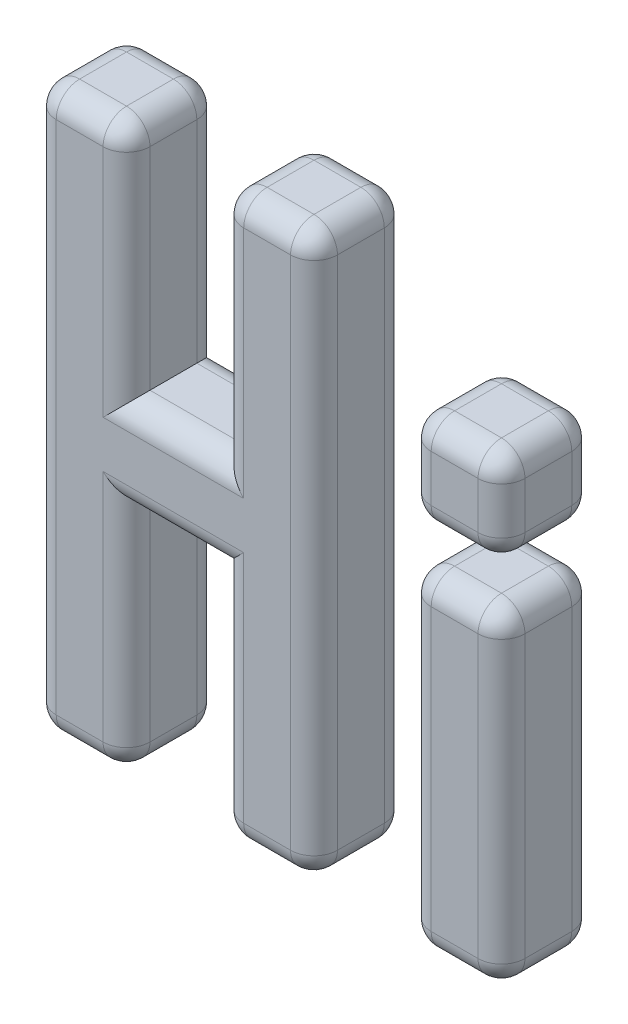
SolidWorks part; units mm, degrees
material "Galvanized Steel"
ref_plane "Front Plane" through (0, 0, 0) normal (0, 0, 1) x (1, 0, 0)
ref_plane "Top Plane" through (0, 0, 0) normal (0, 1, 0) x (1, 0, 0)
ref_plane "Right Plane" through (0, 0, 0) normal (1, 0, 0) x (0, 0, -1)
sketch "Sketch1" plane through (0, 0, 0) normal (0, 0, 1) x (1, 0, 0)
  line L0 (-86.338, 15.2817) -> (-86.338, -9.7183)
  line L1 (-96.338, 50.2817) -> (-66.338, 50.2817)
  line L2 (-96.338, 50.2817) -> (-96.338, -9.7183)
  line L3 (-96.338, -9.7183) -> (-66.338, -9.7183)
  line L4 (-66.338, 50.2817) -> (-66.338, -9.7183)
  line L9 (-96.338, 50.2817) -> (-86.338, 50.2817)
  line L10 (-96.338, 50.2817) -> (-96.338, -9.7183)
  line L11 (-96.338, -9.7183) -> (-86.338, -9.7183)
  line L12 (-86.338, 50.2817) -> (-86.338, 25.2817)
  line L13 (-66.338, 50.2817) -> (-76.338, 50.2817)
  line L14 (-66.338, 50.2817) -> (-66.338, -9.7183)
  line L15 (-66.338, -9.7183) -> (-76.338, -9.7183)
  line L16 (-76.338, 50.2817) -> (-76.338, 25.2817)
  line L17 (-86.338, 25.2817) -> (-76.338, 25.2817)
  line L18 (-96.338, 25.2817) -> (-96.338, 15.2817)
  line L19 (-86.338, 15.2817) -> (-76.338, 15.2817)
  line L20 (-66.338, 25.2817) -> (-66.338, 15.2817)
  line L21 (-56.338, 25.2817) -> (-46.338, 25.2817)
  line L22 (-56.338, 25.2817) -> (-56.338, -9.7183)
  line L23 (-56.338, -9.7183) -> (-46.338, -9.7183)
  line L24 (-46.338, 25.2817) -> (-46.338, -9.7183)
  line L25 (-56.338, 39.6338) -> (-46.338, 39.6338)
  line L26 (-56.338, 39.6338) -> (-56.338, 29.6338)
  line L27 (-56.338, 29.6338) -> (-46.338, 29.6338)
  line L28 (-46.338, 39.6338) -> (-46.338, 29.6338)
  line L29 (-76.338, 15.2817) -> (-76.338, -9.7183)
  dimension "D1" = 30
  dimension "D2" = 60
  dimension "D3" = 10
  dimension "D4" = 10
  dimension "D5" = 25
  dimension "D6" = 25
  dimension "D7" = 10
  dimension "D8" = 10
  dimension "D9" = 35
  dimension "D10" = 10
  dimension "D11" = 10
extrude "Boss-Extrude1" add sketch "Sketch1" along normal blind 10 contours L19 L29 L3 L4 L14 L1 L16 L17 L12 L2 L10 L0 | L28 L25 L26 L27 | L24 L21 L22 L23
fillet "Fillet2" radius 2.5 1 edges at (-96.338, 50.2817, 5)
fillet "Fillet3" radius 2.5 1 edges at (-86.338, 50.2817, 5)
fillet "Fillet4" radius 2.5 1 edges at (-66.338, 50.2817, 5)
fillet "Fillet5" radius 2.5 1 edges at (-76.338, 50.2817, 5)
fillet "Fillet6" radius 2.5 1 edges at (-96.338, -9.7183, 5)
fillet "Fillet7" radius 2.5 1 edges at (-86.338, -9.7183, 5)
fillet "Fillet8" radius 2.5 1 edges at (-46.338, -9.7183, 5)
fillet "Fillet9" radius 2.5 1 edges at (-66.338, -9.7183, 5)
fillet "Fillet10" radius 2.5 1 edges at (-76.338, -9.7183, 5)
fillet "Fillet11" radius 2.5 1 edges at (-56.338, -9.7183, 5)
fillet "Fillet12" radius 2.5 1 edges at (-46.338, 25.2817, 5)
fillet "Fillet13" radius 2.5 1 edges at (-46.338, 29.6338, 5)
fillet "Fillet14" radius 2.5 3 edges at (-56.338, 29.6338, 5) (-56.338, 39.6338, 5) (-46.338, 39.6338, 5)
fillet "Fillet15" radius 2.5 1 edges at (-56.338, 25.2817, 5)
fillet "Fillet16" radius 2.5 9 edges at (-86.338, 36.5317, 10) (-87.0703, 49.5495, 10) (-91.338, 50.2817, 10) (-95.6058, 49.5495, 10) (-86.338, 4.0317, 10) (-87.0703, -8.9861, 10) (-91.338, -9.7183, 10) (-95.6058, -8.9861, 10) (-96.338, 20.2817, 10)
fillet "Fillet17" radius 2.5 9 edges at (-76.338, 4.0317, 10) (-66.338, 20.2817, 10) (-67.0703, 49.5495, 10) (-76.338, 36.5317, 10) (-71.338, 50.2817, 10) (-75.6058, 49.5495, 10) (-67.0703, -8.9861, 10) (-71.338, -9.7183, 10) (-75.6058, -8.9861, 10)
fillet "Fillet18" radius 2.5 8 edges at (-47.0703, 24.5495, 10) (-51.338, 25.2817, 10) (-55.6058, 24.5495, 10) (-55.6058, -8.9861, 10) (-51.338, -9.7183, 10) (-47.0703, -8.9861, 10) (-56.338, 7.7817, 10) (-46.338, 7.7817, 10)
fillet "Fillet19" radius 2.5 8 edges at (-55.6058, 38.9016, 10) (-56.338, 34.6338, 10) (-55.6058, 30.366, 10) (-47.0703, 30.366, 10) (-46.338, 34.6338, 10) (-47.0703, 38.9016, 10) (-51.338, 29.6338, 10) (-51.338, 39.6338, 10)
fillet "Fillet20" radius 2.5 8 edges at (-47.0703, 38.9016, 0) (-55.6058, 38.9016, 0) (-56.338, 34.6338, 0) (-55.6058, 30.366, 0) (-51.338, 29.6338, 0) (-47.0703, 30.366, 0) (-51.338, 39.6338, 0) (-46.338, 34.6338, 0)
fillet "Fillet21" radius 2.5 8 edges at (-47.0703, 24.5495, 0) (-51.338, 25.2817, 0) (-55.6058, 24.5495, 0) (-55.6058, -8.9861, 0) (-51.338, -9.7183, 0) (-47.0703, -8.9861, 0) (-56.338, 7.7817, 0) (-46.338, 7.7817, 0)
fillet "Fillet22" radius 2.5 17 edges at (-86.338, 36.5317, 0) (-87.0703, 49.5495, 0) (-91.338, 50.2817, 0) (-95.6058, 49.5495, 0) (-86.338, 4.0317, 0) (-87.0703, -8.9861, 0) (-91.338, -9.7183, 0) (-95.6058, -8.9861, 0) (-76.338, 36.5317, 0) (-75.6058, 49.5495, 0) (-67.0703, 49.5495, 0) (-76.338, 4.0317, 0) (-75.6058, -8.9861, 0) (-71.338, -9.7183, 0) (-67.0703, -8.9861, 0) (-96.338, 20.2817, 0) (-66.338, 20.2817, 0)
fillet "Fillet23" radius 2.5 2 edges at (-81.338, 15.2817, 0) (-81.338, 25.2817, 0)
fillet "Fillet24" radius 2.5 2 edges at (-81.338, 15.2817, 10) (-81.338, 25.2817, 10)
